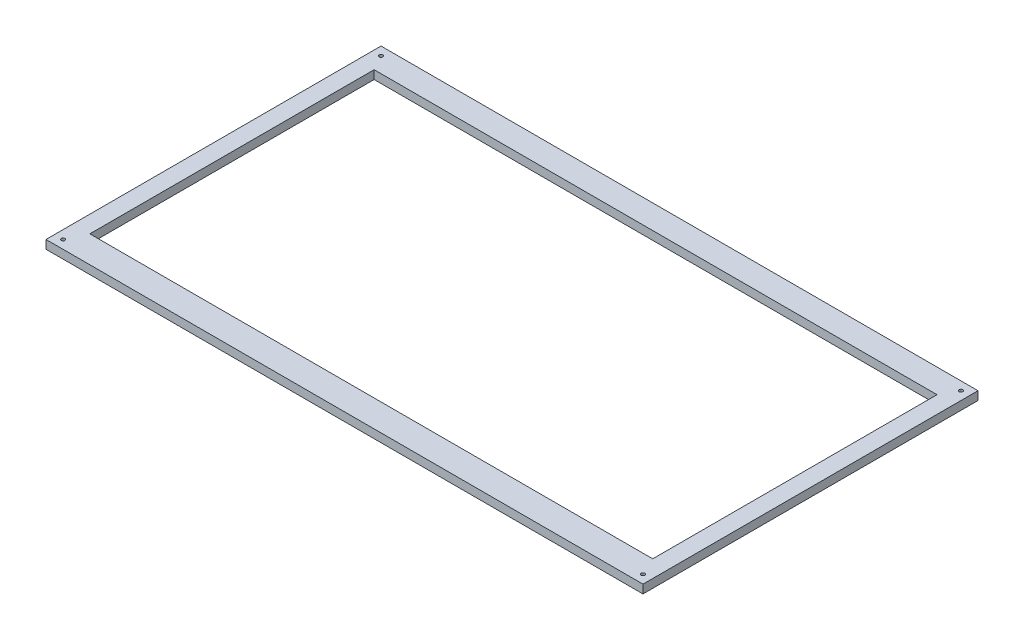
SolidWorks part; units mm, degrees
ref_plane "Front Plane" through (0, 0, 0) normal (0, 0, 1) x (1, 0, 0)
ref_plane "Top Plane" through (0, 0, 0) normal (0, 1, 0) x (1, 0, 0)
ref_plane "Right Plane" through (0, 0, 0) normal (1, 0, 0) x (0, 0, -1)
sketch "Sketch1" plane through (0, 0, 0) normal (0, 1, 0) x (1, 0, 0)
  line L0 (-1050, 589.25) -> (1050, 589.25)
  line L1 (1050, 589.25) -> (1050, -589.25)
  line L2 (-1050, 589.25) -> (-1050, -589.25)
  line L3 (-1050, -589.25) -> (1050, -589.25)
  line L4 (-990, 505) -> (990, 505)
  line L5 (990, 505) -> (990, -495)
  line L6 (990, -495) -> (-990, -495)
  line L7 (-990, -495) -> (-990, 505)
  line L8 (-990, -495) -> (990, -495) construction
  line L9 (1050, -589.25) -> (1050, 589.25) construction
  line L10 (990, 505) -> (-990, 505) construction
  line L12 (990, -495) -> (990, 505) construction
  line L16 (-990, -495) -> (-990, 505) construction
  line L17 (-1050, 589.25) -> (1050, 589.25) construction
  dimension "D1" = 2100
  dimension "D2" = 1178.5
extrude "Boss-Extrude1" add sketch "Sketch1" against normal blind 30
sketch "Sketch2" plane through (0, 0, 0) normal (0, 1, 0) x (1, 0, 0)
  line L0 (0, 589.25) -> (0, -589.25) construction
  line L1 (1050, 589.25) -> (-1050, 589.25) construction
  line L2 (-1050, -589.25) -> (1050, -589.25) construction
  line L3 (-1050, 0) -> (1050, 0) construction
  line L4 (-1050, 589.25) -> (-1050, -589.25) construction
  line L5 (1050, -589.25) -> (1050, 589.25) construction
  circle A0 centre (-1020, 559.25) radius 6.35
  circle A1 centre (-1020, -559.25) radius 6.35
  circle A2 centre (1020, 559.25) radius 6.35
  circle A3 centre (1020, -559.25) radius 6.35
  point P18 (-1020, 559.25)
  dimension "D1" = 12.7
  dimension "D2" = 30
  dimension "D3" = 30
extrude "Cut-Extrude1" cut sketch "Sketch2" against normal through all from surface at 0 starting at face at (0, 0, -5)
equation "\"absorber_plate_width\" = 1000mm"
equation "\"absorber_plate_length\" = 2000mm"
equation "\"absorber_plate_thickness\" = 4mm"
equation "\"groove_depth\" = 10mm"
equation "\"frame_thickness\" = 60mm"
equation "\"insulation_thickness\" = 50mm"
equation "\"glass_thickness\" = 3mm"
equation "\"pipe_distances\" = 100mm"
equation "\"pipe_OD\" = 8.5mm"
equation "\"pipe_ID\" = 7.8mm"
equation "\"pipe_straight_length\" = 850mm"
equation "\"absorber_to_glass\" = 25mm"
equation "\"D1@Sketch1\"=\"absorber_plate_length\"+\"frame_thickness\"*2-\"groove_depth\"*2"
equation "\"D2@Sketch1\"=\"absorber_plate_width\"-\"pipe_distances\"/2+\"pipe_OD\"+\"frame_thickness\"*2+\"insulation_thickness\"*2"
